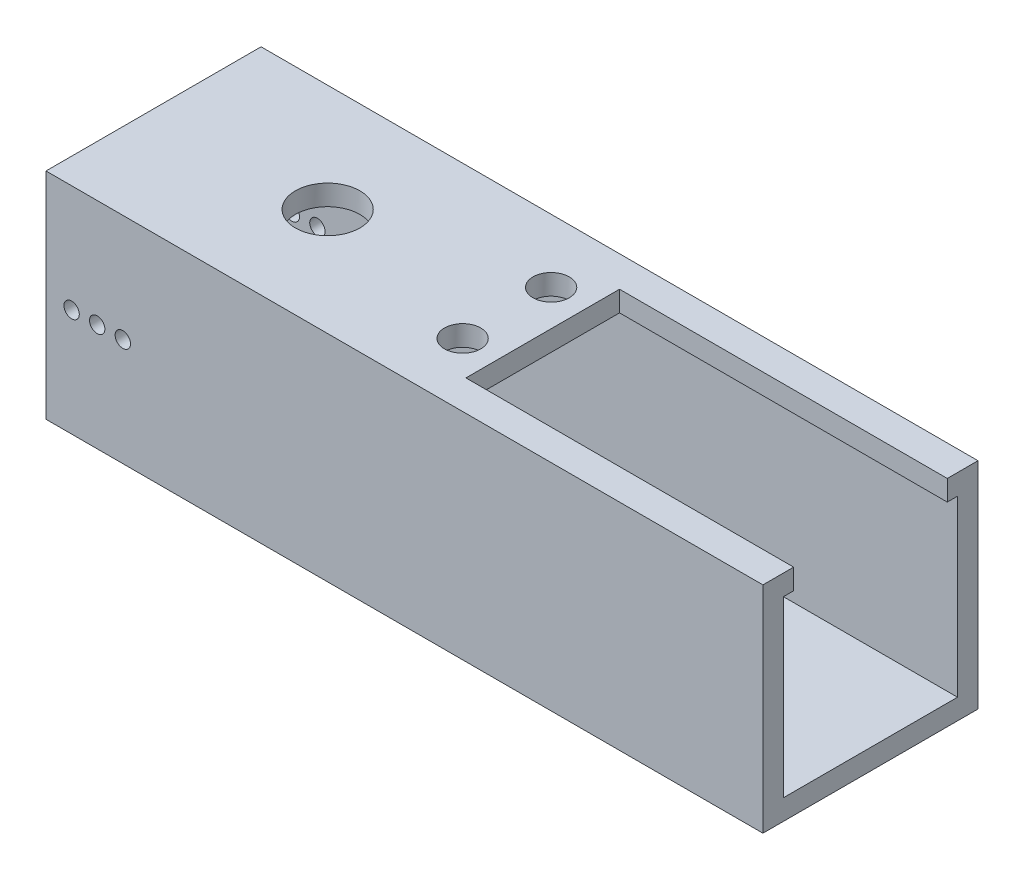
SolidWorks part; units mm, degrees
ref_plane "Front Plane" through (0, 0, 0) normal (0, 0, 1) x (1, 0, 0)
ref_plane "Top Plane" through (0, 0, 0) normal (0, 1, 0) x (1, 0, 0)
ref_plane "Right Plane" through (0, 0, 0) normal (1, 0, 0) x (0, 0, -1)
sketch "Sketch1" plane through (0, 0, 0) normal (1, 0, 0) x (0, 0, -1)
  line L0 (-10.795, 10.795) -> (10.795, 10.795)
  line L1 (-13.335, -13.335) -> (13.335, -13.335)
  line L2 (-13.335, -13.335) -> (-13.335, 13.335)
  line L3 (-13.335, 13.335) -> (13.335, 13.335)
  line L4 (13.335, -13.335) -> (13.335, 13.335)
  line L5 (-13.335, -13.335) -> (13.335, 13.335) construction
  line L6 (-13.335, 13.335) -> (13.335, -13.335) construction
  line L7 (10.795, -10.795) -> (10.795, 10.795)
  line L8 (-10.795, -10.795) -> (10.795, -10.795)
  line L9 (-10.795, -10.795) -> (-10.795, 10.795)
  point P0 (0, 0)
  dimension "D1" = 26.67
  dimension "D2" = 26.67
  dimension "D3" = 2.54
extrude "Boss-Extrude1" add sketch "Sketch1" along normal blind 88.9
sketch "Sketch2" plane through (0, 13.335, 0) normal (0, 1, 0) x (1, 0, 0)
  line L1 (88.9, 13.335) -> (88.9, -13.335) construction
  circle A0 centre (21.59, 0) radius 4.0005
  dimension "D1" = 67.31
  dimension "D2" = 8.001
extrude "Cut-Extrude1" cut sketch "Sketch2" against normal through all
sketch "Sketch3" plane through (0, 13.335, 0) normal (0, 1, 0) x (1, 0, 0)
  line L0 (88.9, 13.335) -> (88.9, -13.335) construction
  line L1 (48.26, 9.525) -> (88.9, 9.525)
  line L2 (48.26, 9.525) -> (48.26, -9.525)
  line L3 (48.26, -9.525) -> (88.9, -9.525)
  line L5 (88.9, 9.525) -> (88.9, -9.525)
  line L7 (88.9, 13.335) -> (0, 13.335) construction
  circle A0 centre (43.815, 5.4877) radius 2.25
  circle A1 centre (43.815, -5.4877) radius 2.25
  dimension "D1" = 40.64
  dimension "D2" = 19.05
  dimension "D3" = 3.81
  dimension "D4" = 4.445
extrude "Cut-Extrude2" cut sketch "Sketch3" against normal up to next
sketch "Sketch4" plane through (0, 0, 13.335) normal (0, 0, 1) x (1, 0, 0)
  line L0 (12.7, 0) -> (0, 0) construction
  line L1 (12.7, 13.335) -> (12.7, -13.335) construction
  line L2 (88.9, 13.335) -> (0, 13.335) construction
  line L3 (88.9, -13.335) -> (0, -13.335) construction
  line L7 (0, 13.335) -> (0, -13.335) construction
  circle A0 centre (6.35, 0) radius 0.9525
  circle A1 centre (3.175, 0) radius 0.9525
  circle A2 centre (9.525, 0) radius 0.9525
  dimension "D1" = 1.905
  dimension "D2" = 3.175
  dimension "D3" = 3.175
  dimension "D4" = 3.175
extrude "Cut-Extrude3" cut sketch "Sketch4" against normal through all
